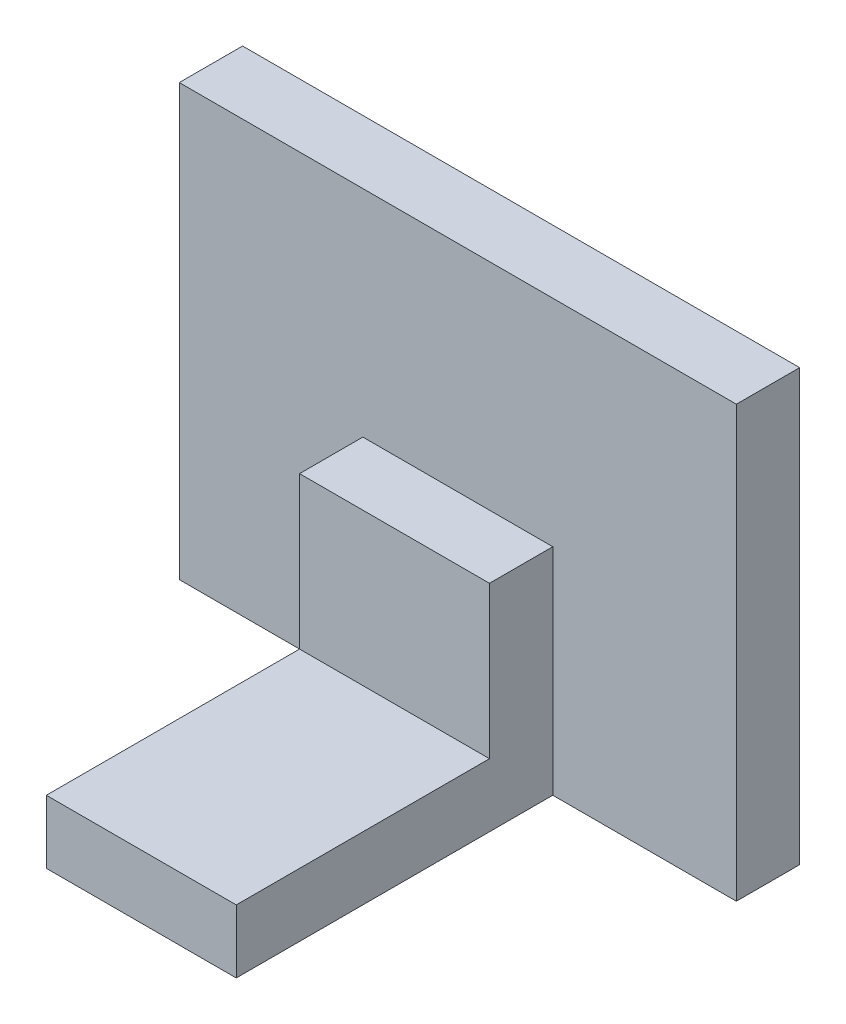
SolidWorks part; units mm, degrees
ref_plane "정면" through (0, 0, 0) normal (0, 0, 1) x (1, 0, 0)
ref_plane "윗면" through (0, 0, 0) normal (0, 1, 0) x (1, 0, 0)
ref_plane "우측면" through (0, 0, 0) normal (1, 0, 0) x (0, 0, -1)
sketch "스케치1" plane through (0, 0, 0) normal (0, 0, 1) x (1, 0, 0)
  line L1 (-22, 17) -> (22, 17)
  line L2 (-22, 17) -> (-22, -17)
  line L3 (-22, -17) -> (22, -17)
  line L4 (22, 17) -> (22, -17)
  line L5 (-22, 17) -> (22, -17) construction
  line L6 (-22, -17) -> (22, 17) construction
  point P0 (0, 0)
  dimension "D1" = 34
  dimension "D2" = 44
extrude "보스-돌출1" add sketch "스케치1" along normal blind 5
sketch "스케치2" plane through (0, 0, 0) normal (0, 0, -1) x (-1, 0, 0)
  line L1 (-18.5, 13) -> (-11.5, 13)
  line L2 (-18.5, 13) -> (-18.5, -13)
  line L3 (-18.5, -13) -> (-11.5, -13)
  line L4 (-11.5, 13) -> (-11.5, -13)
  line L5 (-18.5, 13) -> (-11.5, -13) construction
  line L6 (-18.5, -13) -> (-11.5, 13) construction
  point P0 (-15, 0)
  dimension "D1" = 7
  dimension "D2" = 26
  dimension "D3" = 15
extrude "보스-돌출2" add sketch "스케치2" along normal blind 1
mirror "대칭 복사1" about plane through (0, 0, 0) normal (1, 0, 0) of "보스-돌출2"
sketch "스케치3" plane through (0, 0, 5) normal (0, 0, 1) x (1, 0, 0)
  line L0 (-22, -17) -> (22, -17) construction
  line L1 (-7.5, 0) -> (7.5, 0)
  line L2 (-7.5, 0) -> (-7.5, -17)
  line L3 (-7.5, -17) -> (7.5, -17)
  line L4 (7.5, 0) -> (7.5, -17)
  dimension "D1" = 15
extrude "보스-돌출3" add sketch "스케치3" along normal blind 5
sketch "스케치4" plane through (0, 0, 10) normal (0, 0, 1) x (1, 0, 0)
  line L0 (-7.5, 0) -> (-7.5, -17) construction
  line L1 (-7.5, -17) -> (7.5, -17)
  line L2 (-7.5, -17) -> (-7.5, -12)
  line L3 (-7.5, -12) -> (7.5, -12)
  line L4 (7.5, -17) -> (7.5, -12)
  line L5 (-7.5, 0) -> (-7.5, -17) construction
  line L6 (7.5, -17) -> (7.5, 0) construction
  dimension "D1" = 5
extrude "보스-돌출4" add sketch "스케치4" along normal blind 20
